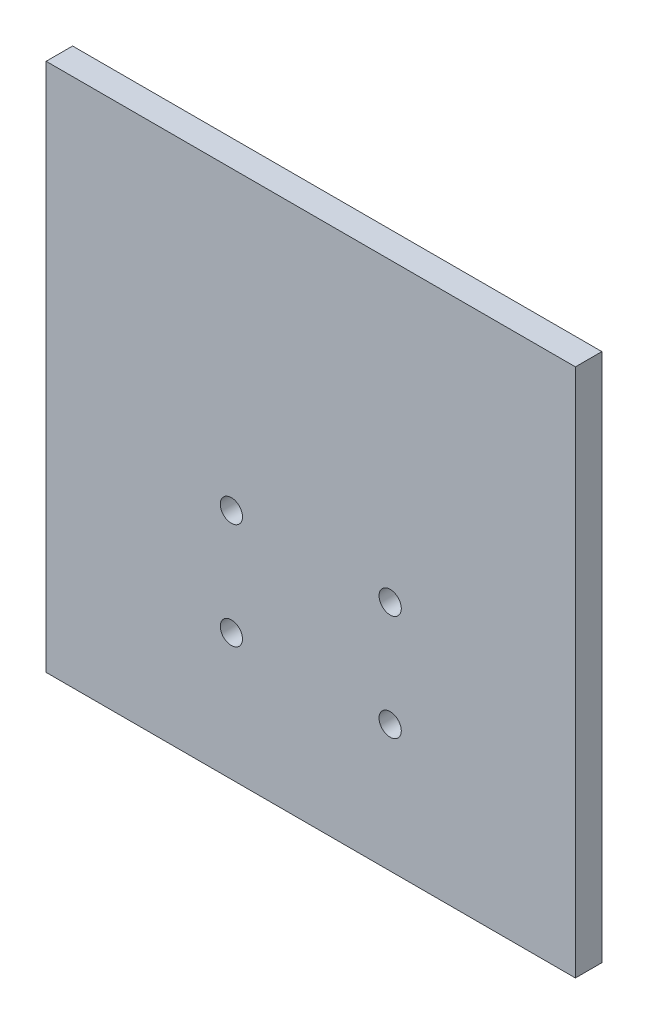
SolidWorks part; units mm, degrees
ref_plane "정면" through (0, 0, 0) normal (0, 0, 1) x (1, 0, 0)
ref_plane "윗면" through (0, 0, 0) normal (0, 1, 0) x (1, 0, 0)
ref_plane "우측면" through (0, 0, 0) normal (1, 0, 0) x (0, 0, -1)
sketch "스케치1" plane through (0, 0, 0) normal (0, 0, 1) x (1, 0, 0)
  line L1 (-50, 50) -> (50, 50)
  line L2 (-50, 50) -> (-50, -50)
  line L3 (-50, -50) -> (50, -50)
  line L4 (50, 50) -> (50, -50)
  line L5 (-50, 50) -> (50, -50) construction
  line L6 (-50, -50) -> (50, 50) construction
  point P0 (0, 0)
  dimension "D1" = 100
  dimension "D2" = 100
extrude "보스-돌출1" add sketch "스케치1" along normal blind 5
sketch "스케치3" plane through (0, 0, 0) normal (0, 0, -1) x (-1, 0, 0)
  text T0 "front"
extrude "컷-돌출2" cut sketch "스케치3" against normal blind 0.001
ref_plane "평면1" through (0, 0, -5) normal (0, 0, -1) x (-1, 0, 0)
hole_wizard "M4x0.7 Helicoil용 탭 구멍1" positions "스케치10" profile "스케치11" tap size "M4x0.7" standard "Helicoil® Metric" end condition through all
sketch "스케치10" plane through (0, 0, -5) normal (0, 0, -1) x (-1, 0, 0)
  line L0 (50, -50) -> (-50, -50) construction
  line L1 (-50, -50) -> (-50, 50) construction
  line L2 (50, 50) -> (50, -50) construction
  point P0 (-15, -26)
  point P2 (15, -26)
  point P4 (-15, -6)
  point P6 (15, -6)
  dimension "D1" = 24
  dimension "D2" = 24
  dimension "D3" = 35
  dimension "D4" = 35
  dimension "D5" = 35
  dimension "D6" = 35
  dimension "D7" = 20
  dimension "D8" = 20
sketch "스케치11" plane through (15, -26, -5) normal (1, 0, 0) x (0, 1, 0)
  line L0 (0, 0) -> (0, 10)
  line L1 (0, 10) -> (2.1, 10)
  line L2 (2.1, 10) -> (2.1, 0)
  line L5 (2.1, 0) -> (0, 0)
  line L11 (0, -6.35) -> (0, 107.95) construction
  dimension "관통 탭 드릴 지름" = 4.2
  dimension "관통 탭 드릴 깊이" = 10
cosmetic thread "구멍 나사산1" parameters "D1"=4.7, "D2"=5.007
cosmetic thread "구멍 나사산2" parameters "D1"=4.7, "D2"=5.007
cosmetic thread "구멍 나사산3" parameters "D1"=4.7, "D2"=5.007
cosmetic thread "구멍 나사산4" parameters "D1"=4.7, "D2"=5.007
